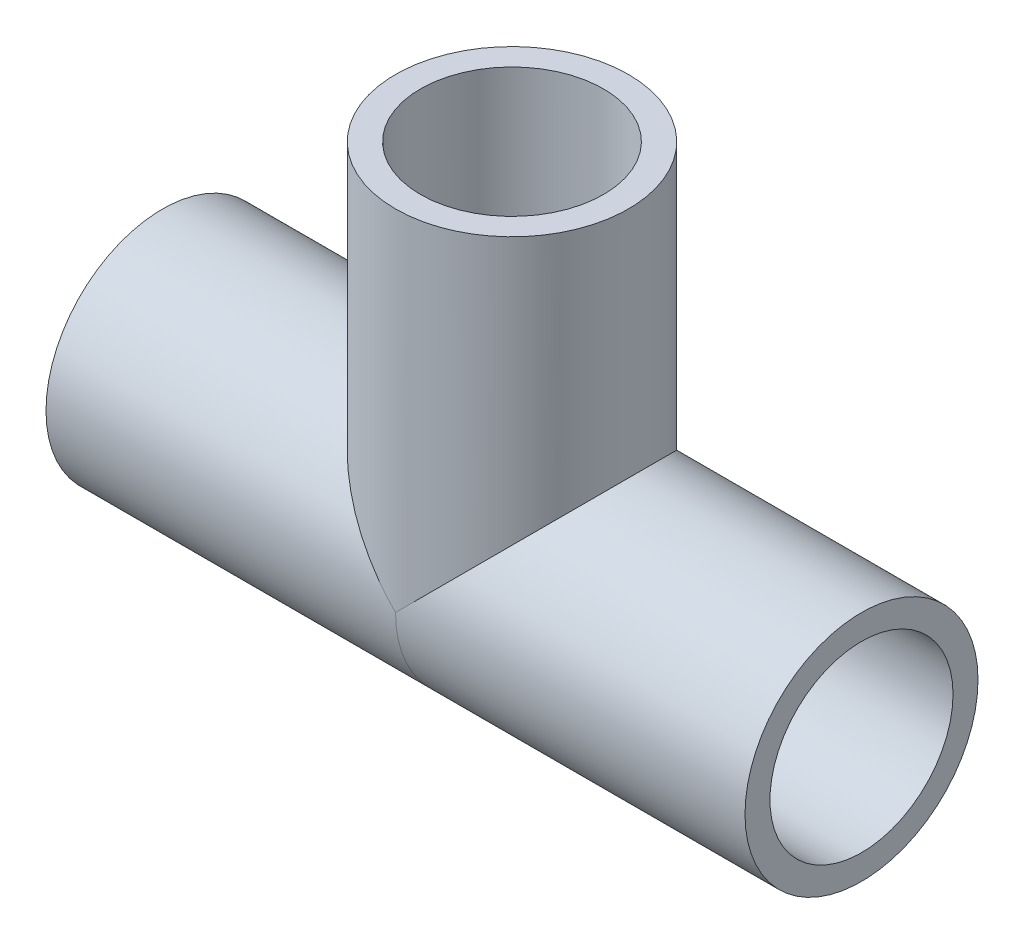
SolidWorks part; units mm, degrees
material "PVC 0.007 Plasticized"
ref_plane "Front Plane" through (0, 0, 0) normal (0, 0, 1) x (1, 0, 0)
ref_plane "Top Plane" through (0, 0, 0) normal (0, 1, 0) x (1, 0, 0)
ref_plane "Right Plane" through (0, 0, 0) normal (1, 0, 0) x (0, 0, -1)
sketch "Sketch1" plane through (0, 0, 0) normal (0, 0, 1) x (1, 0, 0)
  line L1 (0, 0) -> (42, 0)
  line L2 (0, 0) -> (-42, 0)
  point P5 (32, 0)
  point P6 (-32, 0)
ref_plane "Plane1" through (32, 0, 0) normal (1, 0, 0) x (0, 0, -1)
sketch "Sketch3" plane through (32, 0, 0) normal (1, 0, 0) x (0, 0, -1)
  circle A0 centre (0, 0) radius 14
  circle A1 centre (0, 0) radius 11
sweep "Sweep1" add profiles "Sketch3" path "Sketch1"
sketch "Sketch5" plane through (0, 0, 0) normal (0, 1, 0) x (1, 0, 0)
  circle A0 centre (0, 0) radius 14
  circle A1 centre (0, 0) radius 11
extrude "Boss-Extrude1" add sketch "Sketch5" along normal blind 42
sketch "Sketch6" plane through (42, 0, 0) normal (1, 0, 0) x (0, 0, -1)
  circle A0 centre (0, 0) radius 11
  point P3 (0, 0)
extrude "Cut-Extrude1" cut sketch "Sketch6" against normal blind 95
sketch "Sketch7" plane through (0, 42, 0) normal (0, 1, 0) x (1, 0, 0)
  circle A0 centre (0, 0) radius 11
extrude "Cut-Extrude2" cut sketch "Sketch7" against normal blind 33
